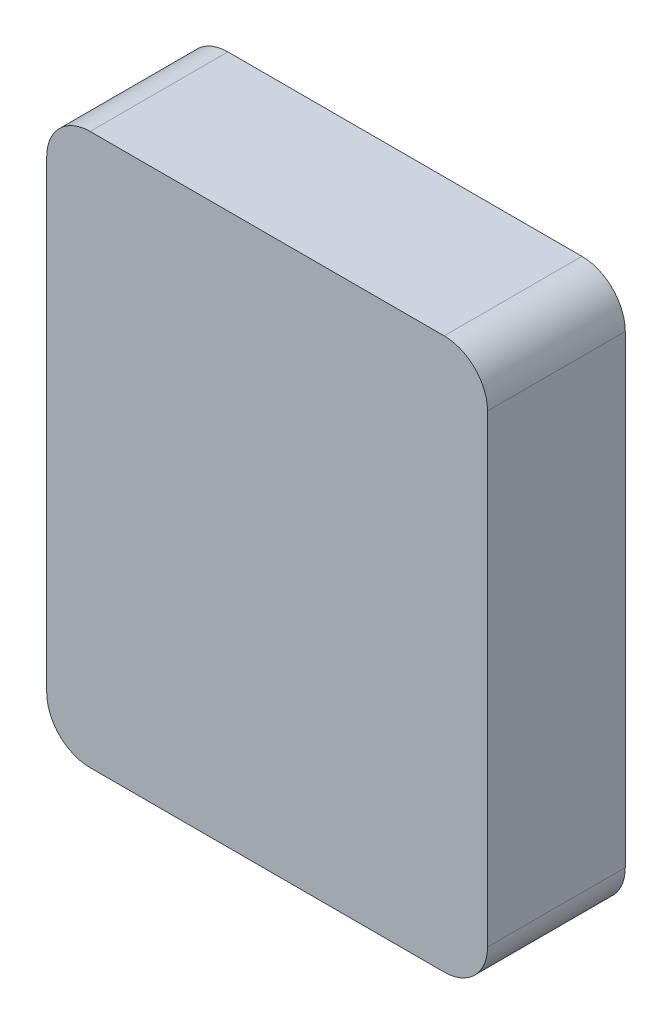
SolidWorks part; units mm, degrees
ref_plane "Front Plane" through (0, 0, 0) normal (0, 0, 1) x (1, 0, 0)
ref_plane "Top Plane" through (0, 0, 0) normal (0, 1, 0) x (1, 0, 0)
ref_plane "Right Plane" through (0, 0, 0) normal (1, 0, 0) x (0, 0, -1)
sketch "Sketch1" plane through (0, 0, 0) normal (0, 0, 1) x (1, 0, 0)
  line L1 (0, 0) -> (101.6, 0)
  line L2 (0, 0) -> (0, 127)
  line L3 (0, 127) -> (101.6, 127)
  line L4 (101.6, 0) -> (101.6, 127)
  dimension "D1" = 127
  dimension "D2" = 101.6
extrude "Boss-Extrude1" add sketch "Sketch1" along normal blind 31.75
fillet "Fillet1" radius 10 4 edges at (0, 0, 15.875) (101.6, 0, 15.875) (101.6, 127, 15.875) (0, 127, 15.875)
